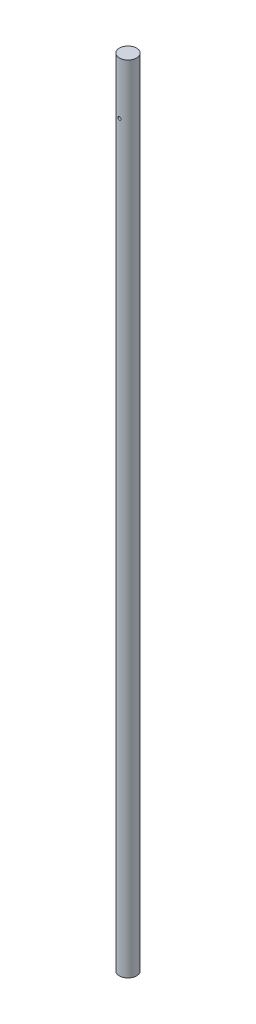
SolidWorks part; units mm, degrees
ref_plane "Front Plane" through (0, 0, 0) normal (0, 0, 1) x (1, 0, 0)
ref_plane "Top Plane" through (0, 0, 0) normal (0, 1, 0) x (1, 0, 0)
ref_plane "Right Plane" through (0, 0, 0) normal (1, 0, 0) x (0, 0, -1)
sketch "Sketch1" plane through (0, 0, 0) normal (0, 1, 0) x (1, 0, 0)
  circle A0 centre (0, 0) radius 16.25
  dimension "D1" = 32.5
extrude "Boss-Extrude1" add sketch "Sketch1" along normal blind 1500
hole_wizard "Ø6.0mm Clearance Dowel Hole1" positions "3DSketch1" profile "Sketch2" hole size "Ø6.0" standard "ISO" end condition through all
sketch3d "3DSketch1"
  circle A0 centre (0, 1500, 0) radius 16.25 construction
  point P0 (0, 1401.3291, 16.25)
  point P5 (0, 1516.25, 0)
  dimension "D1" = 100
sketch "Sketch2" plane through (0, 1401.3291, 16.25) normal (1, 0, 0) x (0, -1, 0)
  line L0 (0, 0) -> (0, 32.5)
  line L1 (0, 32.5) -> (3, 32.5)
  line L2 (3, 32.5) -> (3, 0)
  line L5 (3, 0) -> (0, 0)
  line L11 (0, -6.35) -> (0, 107.95) construction
  dimension "Thru Hole Dia." = 6
  dimension "Thru Hole Depth" = 32.5
